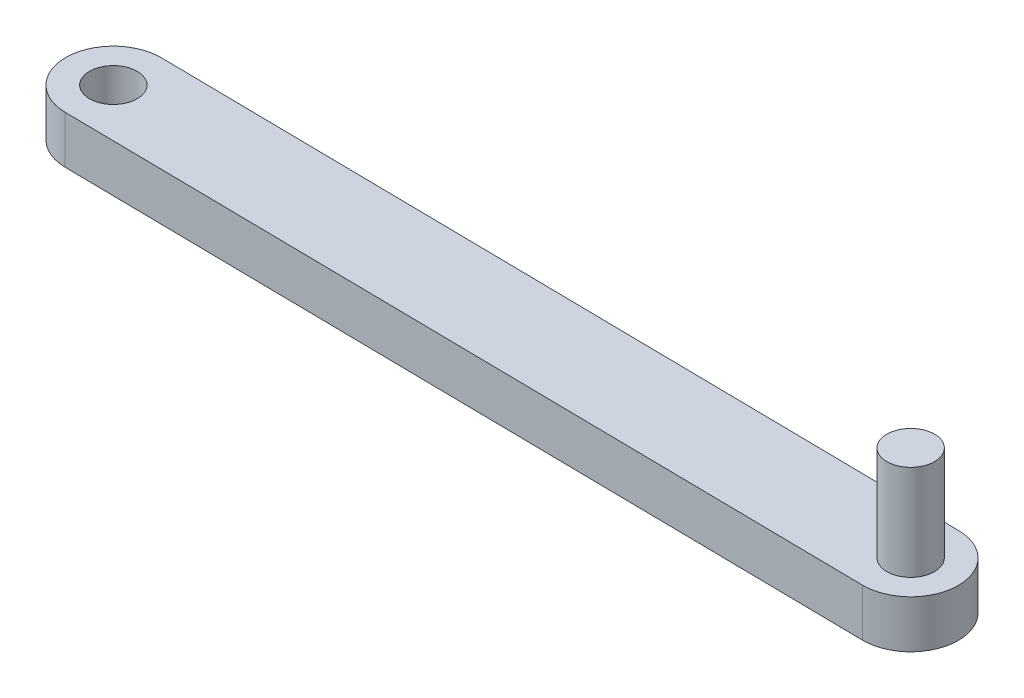
SolidWorks part; units mm, degrees
ref_plane "Front Plane" through (0, 0, 0) normal (0, 0, 1) x (1, 0, 0)
ref_plane "Top Plane" through (0, 0, 0) normal (0, 1, 0) x (1, 0, 0)
ref_plane "Right Plane" through (0, 0, 0) normal (1, 0, 0) x (0, 0, -1)
sketch "Sketch1" plane through (0, 0, 0) normal (0, 1, 0) x (1, 0, 0)
  line L0 (-14.5716, 1.7071) -> (70.2284, 0.5678) construction
  line L1 (-14.5044, 6.7067) -> (70.2956, 5.5674)
  line L2 (-14.6388, -3.2924) -> (70.1612, -4.4317)
  arc A0 (-14.5044, 6.7067) -> (-14.6388, -3.2924) centre (-14.5716, 1.7071) ccw
  arc A1 (70.1612, -4.4317) -> (70.2956, 5.5674) centre (70.2284, 0.5678) ccw
  circle A2 centre (-14.5716, 1.7071) radius 2.5
  point P2 (27.8284, 1.1375)
  dimension "D2" = 5
  dimension "D1" = 84.8
  dimension "D3" = 10
  dimension "D4" = 0
extrude "Boss-Extrude1" add sketch "Sketch1" along normal blind 5
sketch "Sketch2" plane through (0, 5, 0) normal (0, 1, 0) x (1, 0, 0)
  line L0 (-14.6388, -3.2924) -> (70.1612, -4.4317) construction
  circle A0 centre (70.2284, 0.5678) radius 2.5
  circle A1 centre (-14.5716, 1.7071) radius 2.5 construction
  dimension "D2" = 5
  dimension "D1" = 84.8
  dimension "D3" = 5
extrude "Boss-Extrude2" add sketch "Sketch2" along normal blind 10
